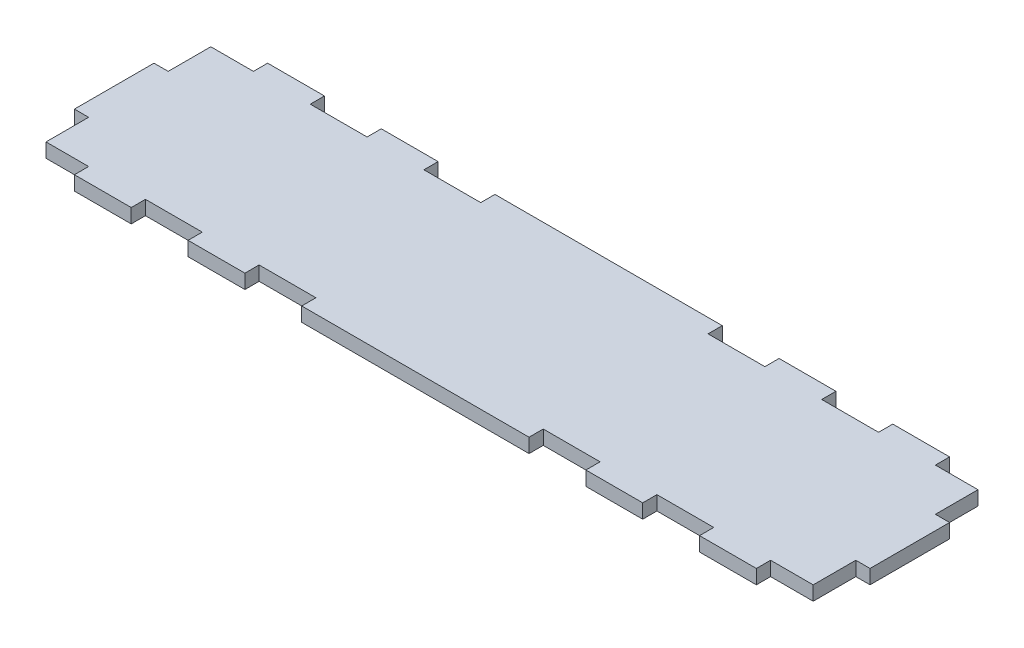
SolidWorks part; units mm, degrees
material "Acrylic (Medium-high impact)"
ref_plane "Front Plane" through (0, 0, 0) normal (0, 0, 1) x (1, 0, 0)
ref_plane "Top Plane" through (0, 0, 0) normal (0, 1, 0) x (1, 0, 0)
ref_plane "Right Plane" through (0, 0, 0) normal (1, 0, 0) x (0, 0, -1)
sketch "Sketch1" plane through (0, 0, 0) normal (0, 1, 0) x (1, 0, 0)
  line L1 (0, 0) -> (171.45, 0)
  line L2 (0, 0) -> (0, 36.83)
  line L3 (0, 36.83) -> (171.45, 36.83)
  line L4 (171.45, 0) -> (171.45, 36.83)
  dimension "D1" = 36.83
  dimension "D2" = 171.45
extrude "Boss-Extrude1" add sketch "Sketch1" along normal blind 3.175
sketch "Sketch2" plane through (0, 3.175, 0) normal (0, 1, 0) x (1, 0, 0)
  line L0 (85.725, 0) -> (85.725, -16.8439) construction
  line L1 (0, 0) -> (171.45, 0) construction
  line L2 (22.225, 0) -> (34.925, 0)
  line L3 (0, 0) -> (-3.175, 0)
  line L4 (0, 0) -> (0, -3.175)
  line L5 (0, -3.175) -> (-3.175, -3.175)
  line L6 (-3.175, 0) -> (-3.175, -3.175)
  line L7 (-3.175, 0) -> (9.525, 0)
  line L8 (-3.175, 0) -> (-3.175, -3.175)
  line L9 (-3.175, -3.175) -> (9.525, -3.175)
  line L10 (9.525, 0) -> (9.525, -3.175)
  line L11 (22.225, 0) -> (22.225, -3.175)
  line L12 (22.225, -3.175) -> (34.925, -3.175)
  line L13 (34.925, 0) -> (34.925, -3.175)
  line L14 (47.625, 0) -> (60.325, 0)
  line L15 (47.625, 0) -> (47.625, -3.175)
  line L16 (47.625, -3.175) -> (60.325, -3.175)
  line L17 (60.325, 0) -> (60.325, -3.175)
  line L18 (-3.175, -3.175) -> (174.625, -3.175)
  line L19 (85.725, -3.175) -> (85.725, 0)
  line L20 (174.625, 0) -> (-3.175, 0)
  line L21 (111.125, 0) -> (111.125, -3.175)
  line L22 (123.825, -3.175) -> (111.125, -3.175)
  line L23 (123.825, 0) -> (123.825, -3.175)
  line L24 (123.825, 0) -> (111.125, 0)
  line L25 (136.525, 0) -> (136.525, -3.175)
  line L26 (149.225, -3.175) -> (136.525, -3.175)
  line L27 (149.225, 0) -> (149.225, -3.175)
  line L28 (161.925, 0) -> (161.925, -3.175)
  line L29 (174.625, -3.175) -> (161.925, -3.175)
  line L30 (174.625, 0) -> (174.625, -3.175)
  line L31 (174.625, 0) -> (161.925, 0)
  line L32 (174.625, 0) -> (174.625, -3.175)
  line L33 (171.45, -3.175) -> (174.625, -3.175)
  line L34 (171.45, 0) -> (171.45, -3.175)
  line L35 (171.45, 0) -> (174.625, 0)
  line L36 (149.225, 0) -> (136.525, 0)
  line M3 (0, 0) -> (171.45, 0)
  dimension "D1" = 3.175
  dimension "D2" = 12.7
  dimension "D3" = 3
extrude "Boss-Extrude2" add sketch "Sketch2" against normal blind 3.175 contours L10 L18 L11 M3 | L13 L18 L15 M3 | L18 L19 L17 M3 | L21 L19 L18 M3 | L25 L23 L18 M3 | L28 L27 L18 M3 | L20
sketch "Sketch3" plane through (0, 3.175, 0) normal (0, 1, 0) x (1, 0, 0)
  line L0 (85.725, -3.175) -> (85.725, 3.175) construction
  line L1 (60.325, -3.175) -> (111.125, -3.175) construction
  line L2 (0, 3.175) -> (171.45, 3.175) construction
  line L3 (0, 36.83) -> (0, 0) construction
  line L4 (171.45, 0) -> (171.45, 36.83) construction
  line L6 (60.325, 0) -> (67.437, 0)
  line L7 (60.325, 0) -> (60.325, 25.654)
  line L8 (60.325, 25.654) -> (67.437, 25.654)
  line L9 (67.437, 0) -> (67.437, 25.654)
  line L10 (111.125, 0) -> (109.855, 0)
  line L11 (111.125, 0) -> (111.125, 29.21)
  line L12 (111.125, 29.21) -> (109.855, 29.21)
  line L13 (109.855, 0) -> (109.855, 29.21)
  line L14 (67.437, 3.175) -> (109.855, 3.175)
  line L15 (67.437, 3.175) -> (67.437, 15.875)
  line L16 (67.437, 15.875) -> (109.855, 15.875)
  line L17 (109.855, 3.175) -> (109.855, 15.875)
  dimension "D1" = 6.35
  dimension "D2" = 7.112
  dimension "D3" = 1.27
  dimension "D4" = 12.7
extrude "Cut-Extrude1" cut sketch "Sketch3" against normal blind 3.175 contours L14 L17 L16 L15
sketch "Sketch5" plane through (0, 3.175, 0) normal (0, 1, 0) x (1, 0, 0)
  line L0 (67.437, 3.175) -> (109.855, 3.175) construction
  line L1 (67.437, 15.875) -> (81.407, 15.875)
  line L2 (67.437, 15.875) -> (67.437, 3.175)
  line L3 (67.437, 3.175) -> (81.407, 3.175)
  line L4 (81.407, 15.875) -> (81.407, 3.175)
  line L5 (67.437, 15.875) -> (109.855, 15.875) construction
  line L6 (109.855, 3.175) -> (98.425, 3.175)
  line L7 (109.855, 3.175) -> (109.855, 15.875)
  line L8 (109.855, 15.875) -> (98.425, 15.875)
  line L9 (98.425, 3.175) -> (98.425, 15.875)
  line L11 (81.407, 15.875) -> (98.425, 15.875)
  line L12 (81.407, 15.875) -> (81.407, 3.175)
  line L13 (81.407, 3.175) -> (98.425, 3.175)
  line L14 (98.425, 15.875) -> (98.425, 3.175)
  line M26 (67.437, 15.875) -> (109.855, 15.875)
  line M28 (109.855, 3.175) -> (67.437, 3.175)
  dimension "D1" = 13.97
  dimension "D2" = 11.43
extrude "Boss-Extrude3" add sketch "Sketch5" against normal blind 3.175 contours L9 L4 M28 M26
sketch "Sketch6" plane through (0, 3.175, 0) normal (0, 1, 0) x (1, 0, 0)
  line L0 (0, 36.83) -> (0, 0) construction
  line L1 (9.525, -3.175) -> (-3.175, -3.175)
  line L2 (9.525, -3.175) -> (9.525, 9.525)
  line L3 (9.525, 9.525) -> (-3.175, 9.525)
  line L4 (-3.175, -3.175) -> (-3.175, 9.525)
  line L5 (161.925, -3.175) -> (174.625, -3.175)
  line L6 (161.925, -3.175) -> (161.925, 9.525)
  line L7 (161.925, 9.525) -> (174.625, 9.525)
  line L8 (174.625, -3.175) -> (174.625, 9.525)
  line L9 (0, 36.83) -> (-3.175, 36.83)
  line L10 (0, 36.83) -> (0, 40.005)
  line L11 (0, 40.005) -> (-3.175, 40.005)
  line L12 (-3.175, 36.83) -> (-3.175, 40.005)
  line L13 (171.45, 36.83) -> (174.625, 36.83)
  line L14 (171.45, 36.83) -> (171.45, 40.005)
  line L15 (171.45, 40.005) -> (174.625, 40.005)
  line L16 (174.625, 36.83) -> (174.625, 40.005)
  line L17 (174.625, 40.005) -> (161.925, 40.005)
  line L18 (174.625, 40.005) -> (174.625, 27.305)
  line L19 (174.625, 27.305) -> (161.925, 27.305)
  line L20 (161.925, 40.005) -> (161.925, 27.305)
  line L21 (-3.175, 40.005) -> (9.525, 40.005)
  line L22 (-3.175, 40.005) -> (-3.175, 27.305)
  line L23 (-3.175, 27.305) -> (9.525, 27.305)
  line L24 (9.525, 40.005) -> (9.525, 27.305)
  line L25 (-3.175, 27.305) -> (0, 27.305)
  line L26 (-3.175, 27.305) -> (-3.175, 9.525)
  line L27 (-3.175, 9.525) -> (0, 9.525)
  line L28 (0, 27.305) -> (0, 9.525)
  line L29 (171.45, 0) -> (171.45, 36.83) construction
  line L30 (174.625, 27.305) -> (171.45, 27.305)
  line L31 (174.625, 27.305) -> (174.625, 9.525)
  line L32 (174.625, 9.525) -> (171.45, 9.525)
  line L33 (171.45, 27.305) -> (171.45, 9.525)
  line M5 (0, 36.83) -> (0, 0)
  line M27 (171.45, 0) -> (171.45, 36.83)
  dimension "D1" = 12.7
  dimension "D2" = 12.7
  dimension "D3" = 12.7
  dimension "D4" = 3.175
  dimension "D5" = 3.175
  dimension "D6" = 12.7
  dimension "D7" = 12.7
extrude "Boss-Extrude4" add sketch "Sketch6" against normal blind 3.175 contours L31 L19 L7 M27 | L23 L26 L3 M5
ref_plane "Plane2" through (0, 0, -18.415) normal (0, 0, -1) x (-1, 0, 0)
mirror "Mirror1" about plane through (0, 0, -18.415) normal (0, 0, -1) of "Boss-Extrude2"
sketch "Sketch7" plane through (0, 3.175, 0) normal (0, 1, 0) x (1, 0, 0)
  line L1 (56.1342, 26.5004) -> (115.4825, 26.5004)
  line L2 (56.1342, 26.5004) -> (56.1342, 1.3273)
  line L3 (56.1342, 1.3273) -> (115.4825, 1.3273)
  line L4 (115.4825, 26.5004) -> (115.4825, 1.3273)
extrude "Boss-Extrude5" add sketch "Sketch7" against normal blind 3.175
